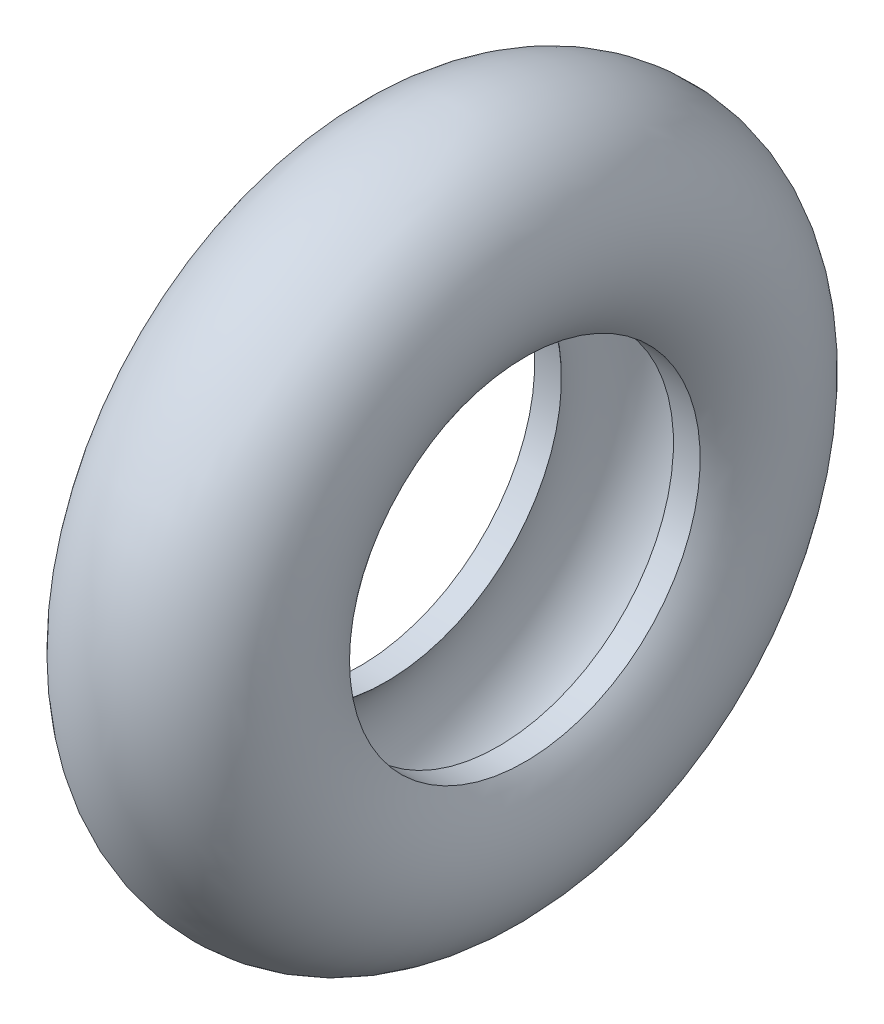
SolidWorks part; units mm, degrees
material "BUTYL"
ref_plane "Plan de face" through (0, 0, 0) normal (0, 0, 1) x (1, 0, 0)
ref_plane "Plan de dessus" through (0, 0, 0) normal (0, 1, 0) x (1, 0, 0)
ref_plane "Plan de droite" through (0, 0, 0) normal (1, 0, 0) x (0, 0, -1)
sketch "Esquisse1" plane through (0, 0, 0) normal (0, 0, 1) x (1, 0, 0)
  line L0 (-106.6081, 0) -> (126.1459, 0) construction
  line L1 (0, 110.4307) -> (0, -134.2158) construction
  line L2 (120.5589, 184.995) -> (-140.6473, 184.995) construction
  line L3 (-43.624, 92.4481) -> (-29.5288, 92.4481)
  line L4 (29.5288, 92.4481) -> (43.624, 92.4481)
  arc A0 (43.624, 92.4481) -> (-43.624, 92.4481) centre (0, 128.44) ccw
  arc A1 (-29.5288, 92.4481) -> (29.5288, 92.4481) centre (0, 128.44) cw
  dimension "D1" = 113.11
  dimension "D5" = 10
  dimension "D2" = 128.44
  dimension "D3" = 184.995
  dimension "D4" = 92.4481
revolve "Révolution1" add sketch "Esquisse1" angle 360 about L0
sketch "Esquisse2" plane through (0, 0, 0) normal (1, 0, 0) x (0, 0, -1)
  circle A0 centre (0, 0) radius 85
  dimension "D1" = 170
